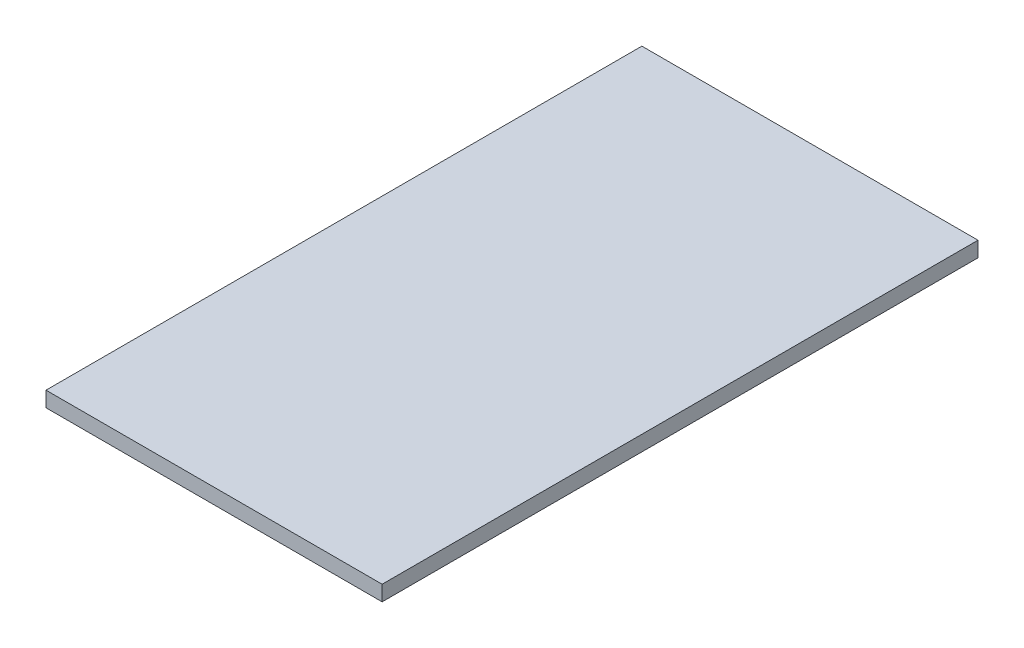
SolidWorks part; units mm, degrees
ref_plane "Front Plane" through (0, 0, 0) normal (0, 0, 1) x (1, 0, 0)
ref_plane "Top Plane" through (0, 0, 0) normal (0, 1, 0) x (1, 0, 0)
ref_plane "Right Plane" through (0, 0, 0) normal (1, 0, 0) x (0, 0, -1)
sketch "Sketch1" plane through (0, 0, 0) normal (0, 1, 0) x (1, 0, 0)
  line L1 (-1.1, 1.95) -> (1.1, 1.95)
  line L2 (-1.1, 1.95) -> (-1.1, -1.95)
  line L3 (-1.1, -1.95) -> (1.1, -1.95)
  line L4 (1.1, 1.95) -> (1.1, -1.95)
  line L5 (-1.1, 1.95) -> (1.1, -1.95) construction
  line L6 (-1.1, -1.95) -> (1.1, 1.95) construction
  point P0 (0, 0)
  dimension "D1" = 3.9
  dimension "D2" = 2.2
extrude "Boss-Extrude1" add sketch "Sketch1" along normal blind 0.1
